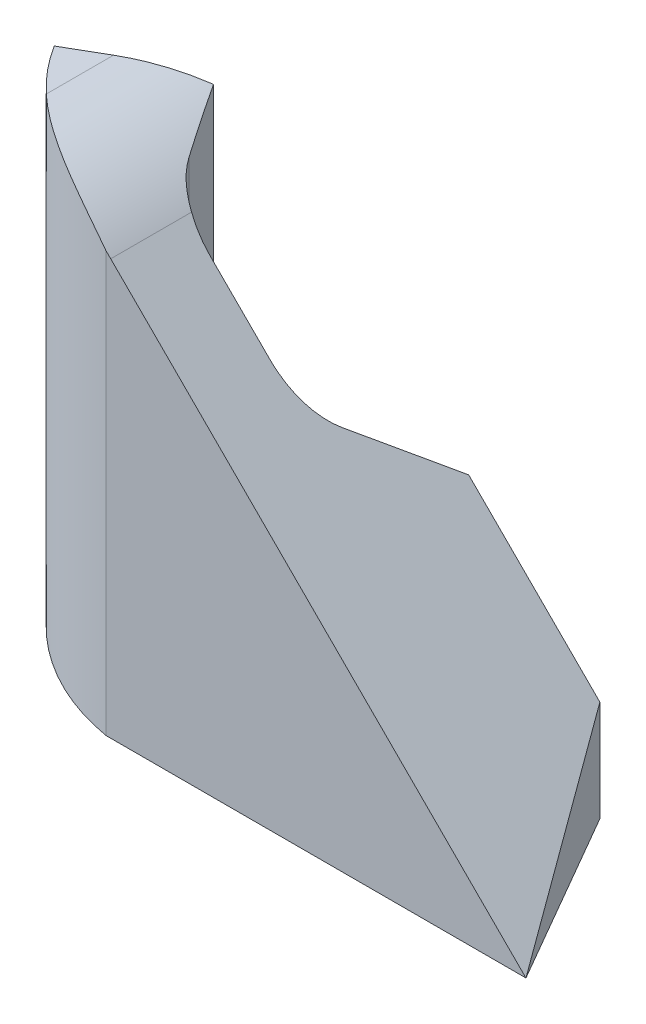
SolidWorks part; units mm, degrees
other "Markup1"
sketch "Sketch26" plane through (25.6218, 0, -129.9038) normal (-0.1134, -0.9932, -0.0259) x (0.9576, -0.1162, 0.2636)
ref_plane "Front Plane" through (0, 0, 0) normal (0, 0, 1) x (1, 0, 0)
ref_plane "Top Plane" through (0, 0, 0) normal (0, 1, 0) x (1, 0, 0)
ref_plane "Right Plane" through (0, 0, 0) normal (1, 0, 0) x (0, 0, -1)
sketch "Sketch1" plane through (0, 0, 0) normal (0, 1, 0) x (1, 0, 0)
  line L0 (0, 0) -> (150, 0)
  line L1 (0, 0) -> (75, 129.9038)
  line L2 (75, 129.9038) -> (150, 0)
  dimension "D1" = 60
  dimension "D2" = 150
  dimension "D3" = 60
sketch "Sketch2" plane through (0, 0, 0) normal (0, 1, 0) x (1, 0, 0)
  line L1 (74, 5) -> (174, 5) construction
  line L2 (74, 5) -> (74, 25) construction
  line L3 (74, 25) -> (174, 25) construction
  line L4 (174, 5) -> (174, 25) construction
  line L5 (41.3301, 61.5859) -> (91.3301, 148.1884) construction
  line L6 (91.3301, 148.1884) -> (108.6506, 138.1884) construction
  line L7 (108.6506, 138.1884) -> (58.6506, 51.5859) construction
  line L8 (58.6506, 51.5859) -> (41.3301, 61.5859) construction
  line L9 (0, 0) -> (150, 0) construction
  line L10 (108.6506, 138.1884) -> (58.6506, 51.5859)
  line L11 (58.6506, 51.5859) -> (41.3301, 61.5859)
  line L12 (41.3301, 61.5859) -> (91.3301, 148.1884)
  line L13 (91.3301, 148.1884) -> (108.6506, 138.1884)
  line L14 (74, 25) -> (174, 25)
  line L15 (174, 5) -> (174, 25)
  line L16 (74, 5) -> (174, 5)
  line L17 (74, 5) -> (74, 25)
  line L18 (0, 0) -> (75, 129.9038) construction
  dimension "D1" = 20
  dimension "D2" = 5
  dimension "D3" = 74
  dimension "D4" = 20
  dimension "D5" = 74
  dimension "D6" = 5
  dimension "D7" = 100
  dimension "D8" = 100
  dimension "D9" = 0
  dimension "D10" = 0
sketch "Sketch4" plane through (0, 0, 0) normal (0, 1, 0) x (1, 0, 0)
  line L5 (41.1191, 35.292) -> (0, 0) construction
  line L6 (0, 0) -> (53.0061, 91.8093) construction
  line L7 (68.4402, 27.9736) -> (51.1204, 17.9723) construction
  line L8 (68.4402, 27.9736) -> (58.4388, 45.2934) construction
  line L9 (58.4388, 45.2934) -> (41.1191, 35.292) construction
  line L10 (51.1204, 17.9723) -> (41.1191, 35.292) construction
  line L11 (68.4402, 27.9736) -> (41.1191, 35.292) construction
  line L12 (58.4388, 45.2934) -> (51.1204, 17.9723) construction
  line L13 (58.4388, 45.2934) -> (41.1191, 35.292)
  line L15 (0, 0) -> (131.24, 0) construction
  line L17 (51.1204, 17.9723) -> (41.1191, 35.292)
  line L18 (68.4402, 27.9736) -> (51.1204, 17.9723)
  line L19 (68.4402, 27.9736) -> (58.4388, 45.2934)
  line L20 (51.1204, 17.9723) -> (0, 0) construction
  point P0 (54.7796, 31.6328)
  dimension "D1" = 20
  dimension "D2" = 20
  dimension "D3" = 21.269
  dimension "D4" = 0
  dimension "D5" = 54.1877
  dimension "D6" = 60
  dimension "D7" = 19.37
ref_plane "Plane1" through (4.3301, 0, 2.5) normal (0.866, 0, 0.5) x (0.5, 0, -0.866)
ref_plane "Plane2" through (21.6506, 0, 12.5) normal (-0.866, 0, -0.5) x (-0.5, 0, 0.866)
ref_plane "Plane3" through (0, 0, -25) normal (0, 0, 1) x (1, 0, 0)
ref_plane "Plane4" through (0, 0, -5) normal (0, 0, 1) x (1, 0, 0)
ref_plane "Plane6" through (-5.0007, 0, -8.6599) normal (-0.5001, 0, -0.866) x (-0.866, 0, 0.5001)
ref_plane "Plane7" through (5.0007, 0, 8.6599) normal (-0.5001, 0, -0.866) x (-0.866, 0, 0.5001)
sketch "Sketch28" plane through (5.0007, 0, 8.6599) normal (-0.5001, 0, -0.866) x (-0.866, 0, 0.5001)
  line L1 (-73.2569, 0) -> (-53.2569, 0)
  line L2 (-73.2569, 0) -> (-73.2569, 80)
  line L3 (-73.2569, 80) -> (-53.2569, 80)
  line L4 (-53.2569, 0) -> (-53.2569, 80)
  dimension "D1" = 80
sketch "Sketch30" plane through (0, 0, 0) normal (0, 1, 0) x (1, 0, 0)
  line L0 (74, 5) -> (174, 5) construction
  line L1 (74, 25) -> (154, 25)
  line L2 (74, 25) -> (74, 5)
  line L3 (74, 5) -> (154, 5)
  line L4 (154, 25) -> (154, 5)
  dimension "D1" = 80
sketch "Sketch31" plane through (0, 0, 0) normal (0, 1, 0) x (1, 0, 0)
  line L10 (78, 0) -> (150, 0)
  line L14 (98.276, 13) -> (82.8598, 13)
  line L15 (74.1999, 17.9993) -> (68.4402, 27.9736)
  line L16 (68.4402, 27.9736) -> (51.1204, 17.9723)
  line L17 (68.4402, 27.9736) -> (58.4388, 45.2934) construction
  line L20 (110.1795, 30) -> (132.6795, 30)
  line L21 (132.6795, 30) -> (150, 0)
  line L22 (110.1795, 30) -> (98.276, 13)
  line L26 (75, 129.9038) -> (150, 0) construction
  line L27 (74, 25) -> (174, 25) construction
  line L28 (0, 0) -> (150, 0) construction
  arc A2 (82.8598, 13) -> (74.1999, 17.9993) centre (82.8598, 23) cw
  arc A5 (51.1204, 17.9723) -> (78, 0) centre (84.7533, 39.1872) ccw
  dimension "D1" = 10
  dimension "D2" = 5
  dimension "D3" = 125
  dimension "D4" = 22.5
  dimension "D5" = 72
  dimension "D6" = 13
extrude "Boss-Extrude1" add sketch "Sketch31" along normal blind 80
sketch "Sketch32" plane through (0, 0, 0) normal (0, 0, 1) x (1, 0, 0)
  line L0 (70, 80) -> (150, 0)
  line L1 (150, 0) -> (150, 80)
  line L2 (150, 80) -> (70, 80)
  dimension "D1" = 45
extrude "Cut-Extrude1" cut sketch "Sketch32" against normal blind 60
sketch "Sketch33" plane through (0, 0, 0) normal (0, 0, 1) x (1, 0, 0)
  line L0 (51.1204, 25) -> (76.1204, 0)
  line L1 (51.1204, 0) -> (51.1204, 80) construction
  line L2 (75, 0) -> (150, 0) construction
  line L3 (76.1204, 0) -> (51.1204, 0)
  line L4 (51.1204, 0) -> (51.1204, 25)
  line L5 (51.1204, 0) -> (0, 0) construction
  line L6 (0, 0) -> (150, 0) construction
  dimension "D1" = 25
  dimension "D2" = 25
extrude "Cut-Extrude2" [suppressed] cut sketch "Sketch33" against normal through all both and the other way through all
fillet "Fillet1" radius 30 5 edges at (69.2201, 80, -26.623) (70, 80, -13.7664) (73.9408, 76.0592, -0.9206) (72.0999, 77.9001, -21.6359) (77.8601, 72.1399, -14.3395)
fillet "Fillet2" [suppressed] radius 10
fillet "Fillet3" radius 10 1 edges at (98.276, 25.862, -13)
